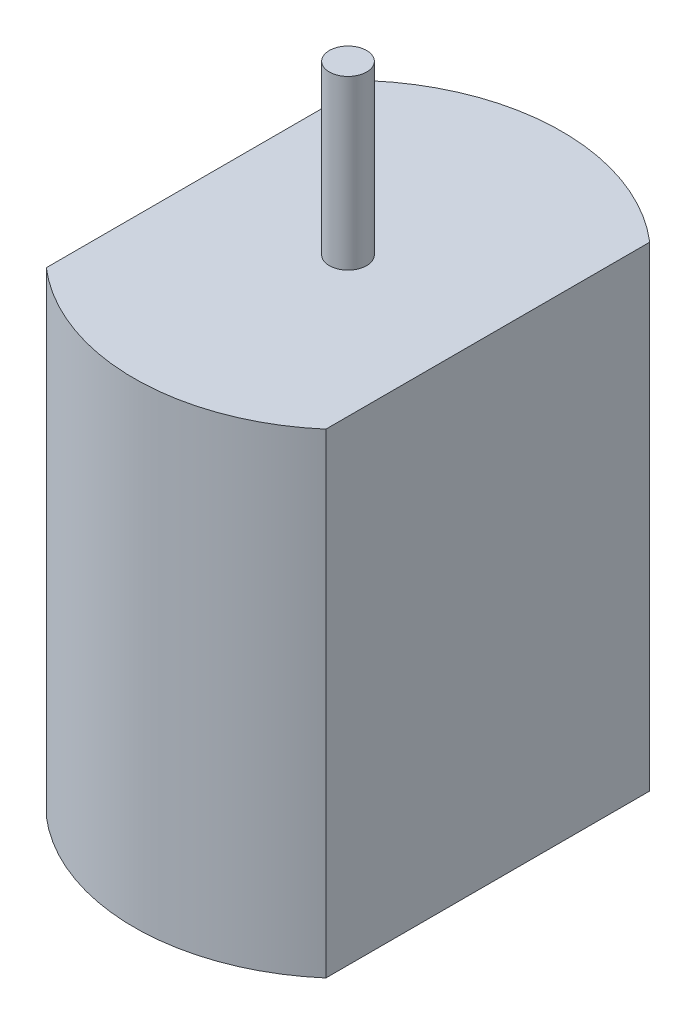
SolidWorks part; units mm, degrees
material "Alumina"
ref_plane "Front Plane" through (0, 0, 0) normal (0, 0, 1) x (1, 0, 0)
ref_plane "Top Plane" through (0, 0, 0) normal (0, 1, 0) x (1, 0, 0)
ref_plane "Right Plane" through (0, 0, 0) normal (1, 0, 0) x (0, 0, -1)
sketch "Sketch1" plane through (0, 0, 0) normal (0, 1, 0) x (1, 0, 0)
  line L0 (0, 11.4762) -> (0, -11.4762)
  line L1 (7.5, 8.6864) -> (7.5, -8.6864)
  line L2 (-7.5, 8.6864) -> (-7.5, -8.6864)
  arc A0 (7.5, 8.6864) -> (-7.5, 8.6864) centre (0, 0) ccw
  arc A1 (-7.5, -8.6864) -> (7.5, -8.6864) centre (0, 0) ccw
  dimension "D1" = 7.5
  dimension "D2" = 7.5
  dimension "D3" = 15
extrude "Boss-Extrude1" add sketch "Sketch1" along normal blind 25.5 contours L0 A1 L1 A0
sketch "Sketch2" plane through (0, 25.5, 0) normal (0, 1, 0) x (1, 0, 0)
  circle A0 centre (0, 0) radius 1
extrude "Boss-Extrude2" add sketch "Sketch2" along normal blind 9
